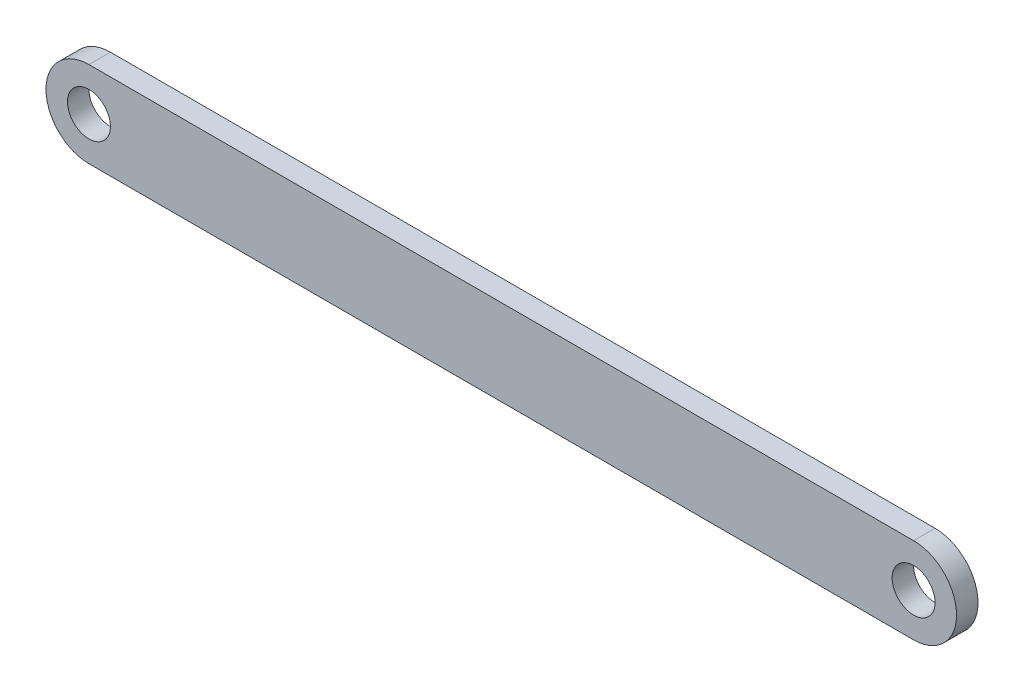
SolidWorks part; units mm, degrees
ref_plane "Front Plane" through (0, 0, 0) normal (0, 0, 1) x (1, 0, 0)
ref_plane "Top Plane" through (0, 0, 0) normal (0, 1, 0) x (1, 0, 0)
ref_plane "Right Plane" through (0, 0, 0) normal (1, 0, 0) x (0, 0, -1)
sketch "Sketch1" plane through (0, 0, 0) normal (0, 0, 1) x (1, 0, 0)
  line L0 (-558.5896, 0.1574) -> (49441.4104, 0.1574) construction
  line L1 (0, 0) -> (0, 71.3201) construction
  line L2 (-609.6, 63.6574) -> (609.6, 63.6574)
  line L3 (-609.6, -63.3426) -> (609.6, -63.3426)
  arc A0 (-609.6, 63.6574) -> (-609.6, -63.3426) centre (-609.6, 0.1574) ccw
  arc A1 (609.6, -63.3426) -> (609.6, 63.6574) centre (609.6, 0.1574) ccw
  circle A2 centre (-609.6, 0.1574) radius 31.75
  circle A3 centre (609.6, 0.1574) radius 31.75
  dimension "D2" = 63.5
  dimension "D3" = 63.5
  dimension "D1" = 1219.2
extrude "Boss-Extrude1" add sketch "Sketch1" along normal mid plane 31.75
